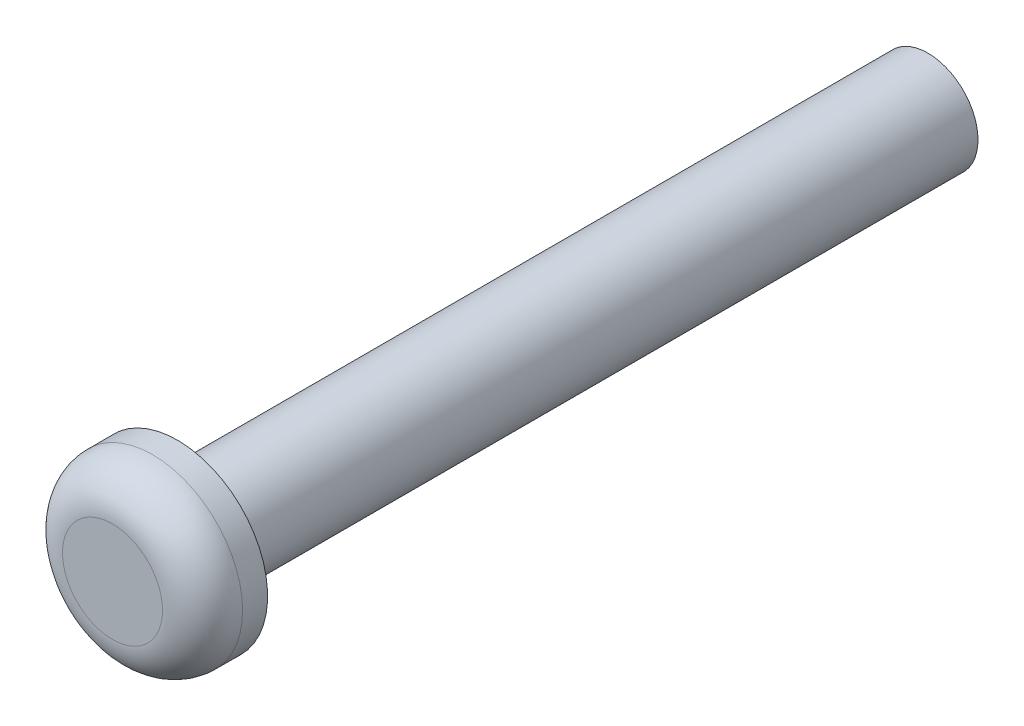
SolidWorks part; units mm, degrees
ref_plane "Front Plane" through (0, 0, 0) normal (0, 0, 1) x (1, 0, 0)
ref_plane "Top Plane" through (0, 0, 0) normal (0, 1, 0) x (1, 0, 0)
ref_plane "Right Plane" through (0, 0, 0) normal (1, 0, 0) x (0, 0, -1)
sketch "Sketch1" plane through (0, 0, 0) normal (0, 0, 1) x (1, 0, 0)
  line L0 (0, 0) -> (0, -86.9685) construction
  line L1 (0, 0) -> (0, 84.2561) construction
  line L2 (0, 0) -> (177.6667, 0) construction
  line L3 (177.6667, 0) -> (-167.4949, 0) construction
  circle A0 centre (0, 0) radius 9
extrude "Boss-Extrude1" add sketch "Sketch1" along normal blind 6.5
fillet "Fillet1" radius 4 1 edges at (9, 0, 6.5)
sketch "Sketch2" plane through (0, 0, 0) normal (0, 0, -1) x (-1, 0, 0)
  circle A0 centre (0, 0) radius 5
extrude "Boss-Extrude2" add sketch "Sketch2" along normal blind 75
sketch "Sketch44" plane through (0, 0, -75) normal (0, 0, -1) x (-1, 0, 0)
  circle A0 centre (0, 0) radius 5
curve "Helix/Spiral1" pitch 2 height 40 turns 20
